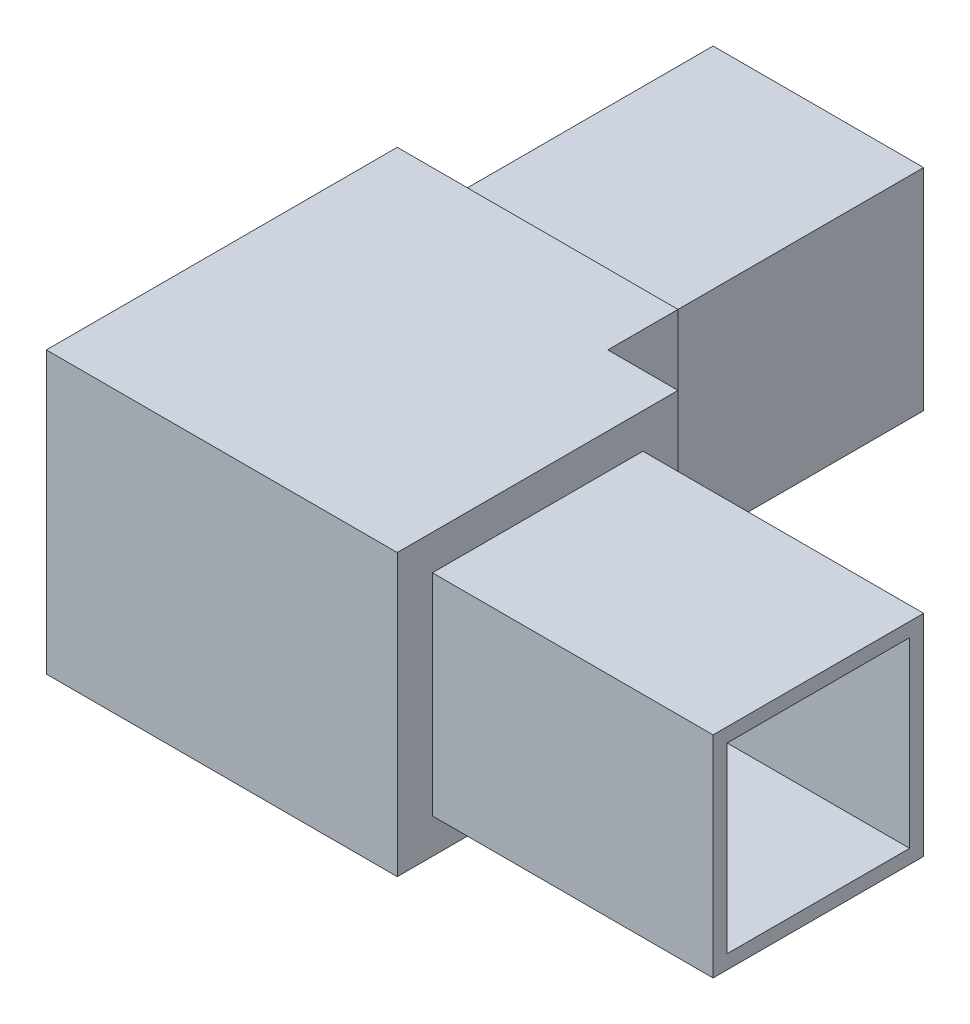
SolidWorks part; units mm, degrees
ref_plane "Alzado" through (0, 0, 0) normal (0, 0, 1) x (1, 0, 0)
ref_plane "Planta" through (0, 0, 0) normal (0, 1, 0) x (1, 0, 0)
ref_plane "Vista lateral" through (0, 0, 0) normal (1, 0, 0) x (0, 0, -1)
sketch "Croquis1" plane through (0, 0, 0) normal (0, 1, 0) x (1, 0, 0)
  line L1 (20, -20) -> (-20, -20)
  line L2 (20, -20) -> (20, 20)
  line L3 (20, 20) -> (-20, 20)
  line L4 (-20, -20) -> (-20, 20)
  line L5 (20, -20) -> (-20, 20) construction
  line L6 (20, 20) -> (-20, -20) construction
  line L7 (20, -20) -> (70, -20)
  line L8 (20, -20) -> (20, 20)
  line L9 (20, 20) -> (70, 20)
  line L10 (70, -20) -> (70, 20)
  line L11 (-20, 20) -> (20, 20)
  line L12 (-20, 20) -> (-20, 70)
  line L13 (-20, 70) -> (20, 70)
  line L14 (20, 20) -> (20, 70)
  point P0 (0, 0)
  dimension "D1" = 40
  dimension "D2" = 40
  dimension "D3" = 50
  dimension "D4" = 50
extrude "Extruir1" add sketch "Croquis1" along normal blind 40 contours L3 L14 L13 L12 | L4 L1 L2 L3 | L7 L10 L9 L2
sketch "Croquis2" plane through (70, 0, 0) normal (1, 0, 0) x (0, 0, -1)
  line L4 (-20, 0) -> (20, 0)
  line L5 (20, 0) -> (20, 40)
  line L6 (20, 40) -> (-20, 40)
  line L7 (-20, 40) -> (-20, 0)
  line L8 (-20, 0) -> (20, 0)
  line L9 (20, 0) -> (20, 40)
  line L10 (20, 40) -> (-20, 40)
  line L11 (-20, 40) -> (-20, 0)
  line L16 (-15, 5) -> (15, 5)
  line L17 (15, 5) -> (15, 35)
  line L18 (15, 35) -> (-15, 35)
  line L19 (-15, 35) -> (-15, 5)
  line L20 (-15, 5) -> (15, 5)
  line L21 (15, 5) -> (15, 35)
  line L22 (15, 35) -> (-15, 35)
  line L23 (-15, 35) -> (-15, 5)
  dimension "D1" = 0
  dimension "D2" = 5
extrude "Extruir2" cut sketch "Croquis2" against normal blind 40
sketch "Croquis3" plane through (0, 0, -70) normal (0, 0, -1) x (-1, 0, 0)
  line L0 (-15, 5) -> (15, 5)
  line L1 (15, 5) -> (15, 35)
  line L2 (15, 35) -> (-15, 35)
  line L3 (-15, 35) -> (-15, 5)
  line L4 (-20, 0) -> (20, 0)
  line L5 (20, 0) -> (20, 40)
  line L6 (20, 40) -> (-20, 40)
  line L7 (-20, 40) -> (-20, 0)
  line L8 (-20, 0) -> (20, 0)
  line L9 (20, 0) -> (20, 40)
  line L10 (20, 40) -> (-20, 40)
  line L11 (-20, 40) -> (-20, 0)
  dimension "D1" = 0
  dimension "D2" = 5
extrude "Extruir3" cut sketch "Croquis3" against normal blind 40
shell "Vaciado1" thickness 2
